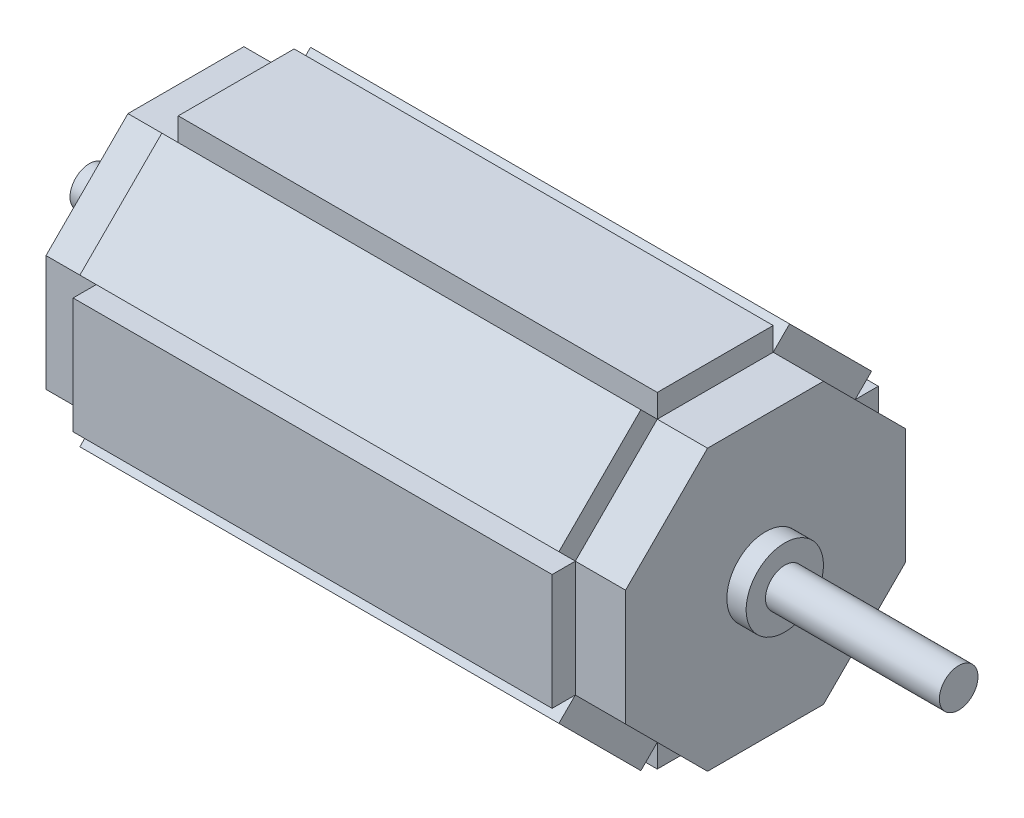
SolidWorks part; units mm, degrees
ref_plane "前视基准面" through (0, 0, 0) normal (0, 0, 1) x (1, 0, 0)
ref_plane "上视基准面" through (0, 0, 0) normal (0, 1, 0) x (1, 0, 0)
ref_plane "右视基准面" through (0, 0, 0) normal (1, 0, 0) x (0, 0, -1)
other "Configuration Table"
sketch "草图1" plane through (0, 0, 0) normal (1, 0, 0) x (0, 0, -1)
  line L1 (7.2426, -3) -> (7.2426, 3)
  line L2 (7.2426, 3) -> (3, 7.2426)
  line L3 (3, 7.2426) -> (-3, 7.2426)
  line L4 (-3, 7.2426) -> (-7.2426, 3)
  line L5 (-7.2426, 3) -> (-7.2426, -3)
  line L6 (-7.2426, -3) -> (-3, -7.2426)
  line L7 (-3, -7.2426) -> (3, -7.2426)
  line L8 (3, -7.2426) -> (7.2426, -3)
  circle A0 centre (0, 0) radius 7.2426 construction
  dimension "D1" = 6
extrude "凸台-拉伸1" add sketch "草图1" along normal blind 30
sketch "草图2" plane through (0, 7.2426, 0) normal (0, 1, 0) x (1, 0, 0)
  line L0 (9.4384, -2.3461) -> (9.352, -2.1662)
  line L1 (9.352, -2.1662) -> (9.8774, -1.7488)
  line L2 (9.8774, -1.7488) -> (9.9997, -1.8064)
  line L3 (11.1224, -1.9863) -> (11.4319, -2.0078)
  line L4 (11.4319, -2.0078) -> (11.6478, -2.0151)
  line L5 (11.6478, -2.0151) -> (11.655, -1.5833)
  line L6 (9.9134, -0.9068) -> (9.8702, -0.7341)
  line L7 (9.8702, -0.7341) -> (10.0933, -0.5901)
  line L8 (10.0933, -0.5901) -> (10.1005, -0.5829)
  line L9 (9.8126, 0.6981) -> (10.2732, 1.1299)
  line L10 (11.6406, 0.7557) -> (11.6765, 0.7629)
  line L11 (11.6765, 0.7629) -> (11.6622, 0.9284)
  line L12 (11.5902, 1.4249) -> (11.9284, 1.684)
  line L13 (11.9284, 1.684) -> (11.5686, 1.7272)
  line L14 (11.5686, 1.7272) -> (10.5467, 1.828)
  line L15 (9.6975, 1.828) -> (9.6399, 1.828)
  line L16 (9.6399, 1.828) -> (9.5247, 2.0151)
  line L17 (9.5247, 2.0151) -> (10.1365, 2.4037)
  line L18 (12.3746, 2.0367) -> (12.5186, 2.051)
  line L19 (12.5186, 2.051) -> (12.5617, 1.8711)
  line L20 (12.5617, 1.8711) -> (12.1515, 1.648)
  line L21 (12.0292, 1.1011) -> (11.9644, 0)
  line L22 (11.9788, -1.9647) -> (11.9788, -2.0294)
  line L23 (11.9788, -2.0294) -> (12.6265, -2.0294)
  line L24 (12.6265, -2.0294) -> (12.6625, -2.159)
  line L25 (12.6625, -2.159) -> (12.2451, -2.4541)
  line L26 (12.3386, -1.6264) -> (12.3962, -1.4897)
  line L27 (13.339, -1.7488) -> (13.3462, -1.3889)
  line L28 (13.3606, -0.6909) -> (12.5761, -0.5829)
  line L29 (12.5761, -0.5829) -> (12.5401, -0.4822)
  line L30 (12.5401, -0.4822) -> (12.8496, -0.2591)
  line L31 (13.2886, 0.3886) -> (13.5261, 0.6621)
  line L32 (12.792, 0.7197) -> (12.7489, 0.8564)
  line L33 (12.7489, 0.8564) -> (12.9216, 0.9715)
  line L34 (12.9216, 0.9715) -> (12.9288, 1.0579)
  line L35 (12.9288, 1.0579) -> (12.9, 1.4249)
  line L36 (12.7057, 2.0655) -> (13.0727, 2.4037)
  line L37 (13.0727, 2.4037) -> (13.1231, 2.3533)
  line L38 (13.4613, 2.1662) -> (13.6197, 2.1302)
  line L39 (14.0802, 2.0583) -> (14.4473, 2.3821)
  line L40 (14.4473, 2.3821) -> (14.548, 2.2741)
  line L41 (14.548, 2.2741) -> (14.5336, 2.2454)
  line L42 (14.3249, 0.5829) -> (14.109, 0.3742)
  line L43 (14.109, 0.3742) -> (14.0011, 0.403)
  line L44 (14.0011, 0.403) -> (14.0011, 0.5757)
  line L45 (14.0011, 0.5757) -> (13.7276, 0.6333)
  line L46 (13.7276, 0.6333) -> (13.6916, 0.5038)
  line L47 (13.6412, -1.7632) -> (13.6485, -1.8279)
  line L48 (13.6485, -1.8279) -> (14.145, -1.9215)
  line L49 (14.1306, -0.4174) -> (14.5984, -0.0648)
  line L50 (14.5984, -0.0648) -> (14.6632, -0.1799)
  line L51 (14.4473, -1.8208) -> (14.4688, -1.9791)
  line L52 (14.4688, -1.9791) -> (14.8935, -2.0223)
  line L53 (14.8935, -2.0223) -> (14.951, -2.1086)
  line L54 (14.951, -2.1086) -> (14.5336, -2.3605)
  line L55 (11.6765, -0.6837) -> (11.6765, 0.4534)
  line L56 (11.2303, 0.511) -> (10.777, 0.5613)
  line L57 (10.777, 0.5613) -> (10.3164, 0.5829)
  line L58 (11.3527, -0.6909) -> (11.6765, -0.6837)
  line L59 (8.6618, -2.4842) -> (8.6618, 2.5158) construction
  spline S0 degree 3 poles (12.2451, -2.4541) (11.9788, -2.3917) (11.4463, -2.2669) (10.5755, -2.2669) knots 0 0 0 0 1 1 1 1
  spline S1 degree 3 poles (10.5755, -2.2669) (10.3955, -2.2669) (10.0357, -2.2669) (9.4384, -2.3461) knots 1 1 1 1 2 2 2 2
  spline S2 degree 3 poles (9.9997, -1.8064) (10.0765, -1.8399) (10.23, -1.9071) (10.669, -1.9503) knots 5 5 5 5 6 6 6 6
  spline S3 degree 3 poles (10.669, -1.9503) (10.7698, -1.9599) (10.9713, -1.9791) (11.1224, -1.9863) knots 6 6 6 6 7 7 7 7
  spline S4 degree 3 poles (11.655, -1.5833) (11.6598, -1.4537) (11.6694, -1.1946) (11.6622, -1.0003) knots 10 10 10 10 11 11 11 11
  spline S5 degree 3 poles (11.6622, -1.0003) (11.4631, -0.962) (11.0648, -0.8852) (10.4315, -0.8852) knots 11 11 11 11 12 12 12 12
  spline S6 degree 3 poles (10.4315, -0.8852) (10.3452, -0.8852) (10.1725, -0.8852) (9.9134, -0.9068) knots 12 12 12 12 13 13 13 13
  spline S7 degree 3 poles (10.1005, -0.5829) (10.0981, -0.523) (10.0933, -0.403) (10.0789, -0.2123) knots 16 16 16 16 17 17 17 17
  spline S8 degree 3 poles (10.0789, -0.2123) (10.0741, -0.1487) (10.0645, -0.0216) (10.0285, 0.1295) knots 17 17 17 17 18 18 18 18
  spline S9 degree 3 poles (10.0285, 0.1295) (10.0165, 0.1967) (9.9925, 0.331) (9.9494, 0.4606) knots 18 18 18 18 19 19 19 19
  spline S10 degree 3 poles (9.9494, 0.4606) (9.9349, 0.5038) (9.9062, 0.5901) (9.8126, 0.6981) knots 19 19 19 19 20 20 20 20
  spline S11 degree 3 poles (10.2732, 1.1299) (10.3356, 1.0675) (10.4603, 0.9428) (10.7194, 0.878) knots 21 21 21 21 22 22 22 22
  spline S12 degree 3 poles (10.7194, 0.878) (10.8417, 0.8468) (11.0864, 0.7844) (11.6406, 0.7557) knots 22 22 22 22 23 23 23 23
  spline S13 degree 3 poles (11.6622, 0.9284) (11.6598, 0.9692) (11.655, 1.0507) (11.6406, 1.1839) knots 25 25 25 25 26 26 26 26
  spline S14 degree 3 poles (11.6406, 1.1839) (11.6358, 1.2283) (11.6262, 1.317) (11.5902, 1.4249) knots 26 26 26 26 27 27 27 27
  spline S15 degree 3 poles (10.5467, 1.828) (10.4747, 1.8351) (10.3308, 1.8495) (10.1221, 1.8495) knots 30 30 30 30 31 31 31 31
  spline S16 degree 3 poles (10.1221, 1.8495) (10.0477, 1.8495) (9.899, 1.8495) (9.6975, 1.828) knots 31 31 31 31 32 32 32 32
  spline S17 degree 3 poles (10.1365, 2.4037) (10.2036, 2.3365) (10.338, 2.2022) (10.6978, 2.1158) knots 35 35 35 35 36 36 36 36
  spline S18 degree 3 poles (10.6978, 2.1158) (10.7793, 2.0966) (10.9425, 2.0583) (11.2879, 2.0367) knots 36 36 36 36 37 37 37 37
  spline S19 degree 3 poles (11.2879, 2.0367) (11.3719, 2.0271) (11.5398, 2.0079) (11.8565, 2.0079) knots 37 37 37 37 38 38 38 38
  spline S20 degree 3 poles (11.8565, 2.0079) (11.9524, 2.0079) (12.1443, 2.0079) (12.3746, 2.0367) knots 38 38 38 38 39 39 39 39
  spline S21 degree 3 poles (12.1515, 1.648) (12.1179, 1.5641) (12.0508, 1.3962) (12.0292, 1.1011) knots 42 42 42 42 43 43 43 43
  spline S22 degree 3 poles (11.9644, 0) (11.962, -0.0911) (11.9572, -0.2735) (11.9572, -0.8132) knots 44 44 44 44 45 45 45 45
  spline S23 degree 3 poles (11.9572, -0.8132) (11.9572, -1.0051) (11.9572, -1.3889) (11.9788, -1.9647) knots 45 45 45 45 46 46 46 46
  spline S24 degree 3 poles (14.5336, -2.3605) (14.3705, -2.2981) (14.0442, -2.1734) (13.0511, -1.8567) knots 0 0 0 0 1 1 1 1
  spline S25 degree 3 poles (13.0511, -1.8567) (12.9719, -1.8327) (12.8136, -1.7848) (12.3386, -1.6264) knots 1 1 1 1 2 2 2 2
  spline S26 degree 3 poles (12.3962, -1.4897) (12.5665, -1.5401) (12.9072, -1.6409) (13.339, -1.7488) knots 3 3 3 3 4 4 4 4
  spline S27 degree 3 poles (13.3462, -1.3889) (13.3534, -1.257) (13.3678, -0.9931) (13.3606, -0.6909) knots 5 5 5 5 6 6 6 6
  spline S28 degree 3 poles (12.8496, -0.2591) (12.8832, -0.2927) (12.9504, -0.3598) (13.0727, -0.4066) knots 9 9 9 9 10 10 10 10
  spline S29 degree 3 poles (13.0727, -0.4066) (13.1135, -0.4222) (13.195, -0.4534) (13.3678, -0.475) knots 10 10 10 10 11 11 11 11
  spline S30 degree 3 poles (13.3678, -0.475) (13.3678, -0.3022) (13.3678, 0.0432) (13.2886, 0.3886) knots 11 11 11 11 12 12 12 12
  spline S31 degree 3 poles (13.5261, 0.6621) (13.3918, 0.6813) (13.1231, 0.7197) (12.792, 0.7197) knots 13 13 13 13 14 14 14 14
  spline S32 degree 3 poles (12.9, 1.4249) (12.8928, 1.4945) (12.8784, 1.6336) (12.8388, 1.7848) knots 18 18 18 18 19 19 19 19
  spline S33 degree 3 poles (12.8388, 1.7848) (12.8256, 1.8351) (12.7993, 1.9359) (12.7057, 2.0655) knots 19 19 19 19 20 20 20 20
  spline S34 degree 3 poles (13.1231, 2.3533) (13.1711, 2.3101) (13.267, 2.2238) (13.4613, 2.1662) knots 22 22 22 22 23 23 23 23
  spline S35 degree 3 poles (13.6197, 2.1302) (13.6916, 2.1134) (13.8355, 2.0798) (14.0802, 2.0583) knots 24 24 24 24 25 25 25 25
  spline S36 degree 3 poles (14.5336, 2.2454) (14.5049, 2.1926) (14.4473, 2.087) (14.4113, 1.9143) knots 28 28 28 28 29 29 29 29
  spline S37 degree 3 poles (14.4113, 1.9143) (14.3969, 1.8472) (14.3681, 1.7128) (14.3465, 1.4897) knots 29 29 29 29 30 30 30 30
  spline S38 degree 3 poles (14.3465, 1.4897) (14.3321, 1.3602) (14.3033, 1.1011) (14.3033, 0.9068) knots 30 30 30 30 31 31 31 31
  spline S39 degree 3 poles (14.3033, 0.9068) (14.3033, 0.854) (14.3033, 0.7484) (14.3249, 0.5829) knots 31 31 31 31 32 32 32 32
  spline S40 degree 3 poles (13.6916, 0.5038) (13.6652, 0.4126) (13.6125, 0.2303) (13.6125, -0.1727) knots 37 37 37 37 38 38 38 38
  spline S41 degree 3 poles (13.6125, -0.1727) (13.6101, -0.2207) (13.6053, -0.3167) (13.6053, -0.5973) knots 38 38 38 38 39 39 39 39
  spline S42 degree 3 poles (13.6053, -0.5973) (13.6053, -0.77) (13.6053, -1.1155) (13.6412, -1.7632) knots 39 39 39 39 40 40 40 40
  spline S43 degree 3 poles (14.145, -1.9215) (14.1546, -1.8663) (14.1738, -1.756) (14.1882, -1.4321) knots 42 42 42 42 43 43 43 43
  spline S44 degree 3 poles (14.1882, -1.4321) (14.193, -1.3458) (14.2026, -1.1731) (14.2026, -1.0507) knots 43 43 43 43 44 44 44 44
  spline S45 degree 3 poles (14.2026, -1.0507) (14.2026, -0.938) (14.2026, -0.7125) (14.1306, -0.4174) knots 44 44 44 44 45 45 45 45
  spline S46 degree 3 poles (14.6632, -0.1799) (14.6296, -0.2303) (14.5624, -0.331) (14.5192, -0.439) knots 47 47 47 47 48 48 48 48
  spline S47 degree 3 poles (14.5192, -0.439) (14.5049, -0.475) (14.4761, -0.5469) (14.4617, -0.7125) knots 48 48 48 48 49 49 49 49
  spline S48 degree 3 poles (14.4617, -0.7125) (14.4521, -0.8084) (14.4329, -1.0003) (14.4329, -1.353) knots 49 49 49 49 50 50 50 50
  spline S49 degree 3 poles (14.4329, -1.353) (14.4329, -1.4561) (14.4329, -1.6624) (14.4473, -1.8208) knots 50 50 50 50 51 51 51 51
  spline S50 degree 3 poles (14.0227, 0.8132) (14.0467, 1.0051) (14.0946, 1.3889) (14.0874, 1.8136) knots 4 4 4 4 5 5 5 5
  spline S51 degree 3 poles (13.2382, 0.9715) (13.3414, 0.9404) (13.5477, 0.878) (14.0227, 0.8132) knots 3 3 3 3 4 4 4 4
  spline S52 degree 3 poles (13.1591, 1.9503) (13.1663, 1.7608) (13.1807, 1.3818) (13.2382, 0.9715) knots 2 2 2 2 3 3 3 3
  spline S53 degree 3 poles (13.6448, 1.8999) (13.5141, 1.9191) (13.2526, 1.9575) (13.1591, 1.9503) knots 1 1 1 1 2 2 2 2
  spline S54 degree 3 poles (14.0874, 1.8136) (14.0706, 1.8231) (14.0371, 1.8424) (13.6448, 1.8999) knots 0 0 0 0 1 1 1 1
  spline S55 degree 3 poles (11.6765, 0.4534) (11.6286, 0.463) (11.5326, 0.4822) (11.2303, 0.511) knots 1 1 1 1 2 2 2 2
  spline S56 degree 3 poles (10.3164, 0.5829) (10.3164, 0.355) (10.3164, -0.1007) (10.4171, -0.5326) knots 4 4 4 4 5 5 5 5
  spline S57 degree 3 poles (10.4171, -0.5326) (10.4555, -0.5494) (10.5323, -0.5829) (10.669, -0.6189) knots 5 5 5 5 6 6 6 6
  spline S58 degree 3 poles (10.669, -0.6189) (10.7194, -0.6309) (10.8201, -0.6549) (11.0001, -0.6693) knots 6 6 6 6 7 7 7 7
  spline S59 degree 3 poles (11.0001, -0.6693) (11.06, -0.6741) (11.18, -0.6837) (11.3527, -0.6909) knots 7 7 7 7 8 8 8 8
  dimension "D1" = 5
sketch "草图3" plane through (0, 7.2426, 0) normal (0, 1, 0) x (1, 0, 0)
  line L0 (16.0742, -2.3589) -> (15.9878, -2.179)
  line L1 (15.9878, -2.179) -> (16.5131, -1.7616)
  line L2 (16.5131, -1.7616) -> (16.6355, -1.8191)
  line L3 (17.7582, -1.999) -> (18.0677, -2.0206)
  line L4 (18.0677, -2.0206) -> (18.2836, -2.0278)
  line L5 (18.2836, -2.0278) -> (18.2908, -1.596)
  line L6 (16.5492, -0.9195) -> (16.506, -0.7468)
  line L7 (16.506, -0.7468) -> (16.7291, -0.6029)
  line L8 (16.7291, -0.6029) -> (16.7363, -0.5957)
  line L9 (16.4484, 0.6853) -> (16.909, 1.1171)
  line L10 (18.2763, 0.7429) -> (18.3123, 0.7501)
  line L11 (18.3123, 0.7501) -> (18.2979, 0.9156)
  line L12 (18.226, 1.4122) -> (18.5642, 1.6713)
  line L13 (18.5642, 1.6713) -> (18.2044, 1.7144)
  line L14 (18.2044, 1.7144) -> (17.1825, 1.8152)
  line L15 (16.3332, 1.8152) -> (16.2757, 1.8152)
  line L16 (16.2757, 1.8152) -> (16.1605, 2.0023)
  line L17 (16.1605, 2.0023) -> (16.7723, 2.3909)
  line L18 (19.0104, 2.0239) -> (19.1544, 2.0383)
  line L19 (19.1544, 2.0383) -> (19.1975, 1.8584)
  line L20 (19.1975, 1.8584) -> (18.7873, 1.6353)
  line L21 (18.665, 1.0883) -> (18.6002, -0.0128)
  line L22 (18.6146, -1.9774) -> (18.6146, -2.0422)
  line L23 (18.6146, -2.0422) -> (19.2623, -2.0422)
  line L24 (19.2623, -2.0422) -> (19.2983, -2.1717)
  line L25 (19.2983, -2.1717) -> (18.8809, -2.4668)
  line L26 (18.9744, -1.6392) -> (19.032, -1.5025)
  line L27 (19.9748, -1.7616) -> (19.9819, -1.4017)
  line L28 (19.9964, -0.7036) -> (19.2119, -0.5957)
  line L29 (19.2119, -0.5957) -> (19.1759, -0.4949)
  line L30 (19.1759, -0.4949) -> (19.4854, -0.2718)
  line L31 (19.9244, 0.3759) -> (20.1619, 0.6493)
  line L32 (19.4278, 0.7069) -> (19.3847, 0.8436)
  line L33 (19.3847, 0.8436) -> (19.5574, 0.9588)
  line L34 (19.5574, 0.9588) -> (19.5646, 1.0451)
  line L35 (19.5646, 1.0451) -> (19.5358, 1.4122)
  line L36 (19.3415, 2.0527) -> (19.7085, 2.3909)
  line L37 (19.7085, 2.3909) -> (19.7589, 2.3406)
  line L38 (20.0971, 2.1534) -> (20.2554, 2.1175)
  line L39 (20.716, 2.0455) -> (21.0831, 2.3693)
  line L40 (21.0831, 2.3693) -> (21.1838, 2.2614)
  line L41 (21.1838, 2.2614) -> (21.1694, 2.2326)
  line L42 (20.9607, 0.5702) -> (20.7448, 0.3615)
  line L43 (20.7448, 0.3615) -> (20.6369, 0.3903)
  line L44 (20.6369, 0.3903) -> (20.6369, 0.563)
  line L45 (20.6369, 0.563) -> (20.3634, 0.6206)
  line L46 (20.3634, 0.6206) -> (20.3274, 0.491)
  line L47 (20.277, -1.7759) -> (20.2842, -1.8407)
  line L48 (20.2842, -1.8407) -> (20.7808, -1.9343)
  line L49 (20.7664, -0.4302) -> (21.2342, -0.0775)
  line L50 (21.2342, -0.0775) -> (21.299, -0.1927)
  line L51 (21.0831, -1.8335) -> (21.1046, -1.9918)
  line L52 (21.1046, -1.9918) -> (21.5292, -2.035)
  line L53 (21.5292, -2.035) -> (21.5868, -2.1214)
  line L54 (21.5868, -2.1214) -> (21.1694, -2.3732)
  line L55 (18.3123, -0.6964) -> (18.3123, 0.4406)
  line L56 (17.8661, 0.4982) -> (17.4127, 0.5486)
  line L57 (17.4127, 0.5486) -> (16.9522, 0.5702)
  line L58 (17.9885, -0.7036) -> (18.3123, -0.6964)
  spline S0 degree 3 poles (18.8809, -2.4668) (18.6146, -2.4044) (18.082, -2.2797) (17.2112, -2.2797) knots 0 0 0 0 1 1 1 1
  spline S1 degree 3 poles (17.2112, -2.2797) (17.0313, -2.2797) (16.6715, -2.2797) (16.0742, -2.3589) knots 1 1 1 1 2 2 2 2
  spline S2 degree 3 poles (16.6355, -1.8191) (16.7123, -1.8527) (16.8658, -1.9199) (17.3048, -1.9631) knots 5 5 5 5 6 6 6 6
  spline S3 degree 3 poles (17.3048, -1.9631) (17.4056, -1.9726) (17.6071, -1.9918) (17.7582, -1.999) knots 6 6 6 6 7 7 7 7
  spline S4 degree 3 poles (18.2908, -1.596) (18.2955, -1.4665) (18.3051, -1.2074) (18.2979, -1.0131) knots 10 10 10 10 11 11 11 11
  spline S5 degree 3 poles (18.2979, -1.0131) (18.0988, -0.9747) (17.7006, -0.898) (17.0673, -0.898) knots 11 11 11 11 12 12 12 12
  spline S6 degree 3 poles (17.0673, -0.898) (16.9809, -0.898) (16.8082, -0.898) (16.5492, -0.9195) knots 12 12 12 12 13 13 13 13
  spline S7 degree 3 poles (16.7363, -0.5957) (16.7339, -0.5357) (16.7291, -0.4158) (16.7147, -0.2251) knots 16 16 16 16 17 17 17 17
  spline S8 degree 3 poles (16.7147, -0.2251) (16.7099, -0.1615) (16.7003, -0.0344) (16.6643, 0.1168) knots 17 17 17 17 18 18 18 18
  spline S9 degree 3 poles (16.6643, 0.1168) (16.6523, 0.184) (16.6283, 0.3183) (16.5851, 0.4478) knots 18 18 18 18 19 19 19 19
  spline S10 degree 3 poles (16.5851, 0.4478) (16.5707, 0.491) (16.542, 0.5774) (16.4484, 0.6853) knots 19 19 19 19 20 20 20 20
  spline S11 degree 3 poles (16.909, 1.1171) (16.9713, 1.0548) (17.0961, 0.93) (17.3552, 0.8652) knots 21 21 21 21 22 22 22 22
  spline S12 degree 3 poles (17.3552, 0.8652) (17.4775, 0.834) (17.7222, 0.7717) (18.2763, 0.7429) knots 22 22 22 22 23 23 23 23
  spline S13 degree 3 poles (18.2979, 0.9156) (18.2955, 0.9564) (18.2908, 1.038) (18.2763, 1.1711) knots 25 25 25 25 26 26 26 26
  spline S14 degree 3 poles (18.2763, 1.1711) (18.2716, 1.2155) (18.2619, 1.3042) (18.226, 1.4122) knots 26 26 26 26 27 27 27 27
  spline S15 degree 3 poles (17.1825, 1.8152) (17.1105, 1.8224) (16.9665, 1.8368) (16.7578, 1.8368) knots 30 30 30 30 31 31 31 31
  spline S16 degree 3 poles (16.7578, 1.8368) (16.6835, 1.8368) (16.5348, 1.8368) (16.3332, 1.8152) knots 31 31 31 31 32 32 32 32
  spline S17 degree 3 poles (16.7723, 2.3909) (16.8394, 2.3238) (16.9737, 2.1894) (17.3336, 2.1031) knots 35 35 35 35 36 36 36 36
  spline S18 degree 3 poles (17.3336, 2.1031) (17.4151, 2.0839) (17.5783, 2.0455) (17.9237, 2.0239) knots 36 36 36 36 37 37 37 37
  spline S19 degree 3 poles (17.9237, 2.0239) (18.0077, 2.0143) (18.1756, 1.9951) (18.4923, 1.9951) knots 37 37 37 37 38 38 38 38
  spline S20 degree 3 poles (18.4923, 1.9951) (18.5882, 1.9951) (18.7801, 1.9951) (19.0104, 2.0239) knots 38 38 38 38 39 39 39 39
  spline S21 degree 3 poles (18.7873, 1.6353) (18.7537, 1.5513) (18.6866, 1.3834) (18.665, 1.0883) knots 42 42 42 42 43 43 43 43
  spline S22 degree 3 poles (18.6002, -0.0128) (18.5978, -0.1039) (18.593, -0.2862) (18.593, -0.826) knots 44 44 44 44 45 45 45 45
  spline S23 degree 3 poles (18.593, -0.826) (18.593, -1.0179) (18.593, -1.4017) (18.6146, -1.9774) knots 45 45 45 45 46 46 46 46
  spline S24 degree 3 poles (21.1694, -2.3732) (21.0063, -2.3109) (20.68, -2.1862) (19.6869, -1.8695) knots 0 0 0 0 1 1 1 1
  spline S25 degree 3 poles (19.6869, -1.8695) (19.6077, -1.8455) (19.4494, -1.7975) (18.9744, -1.6392) knots 1 1 1 1 2 2 2 2
  spline S26 degree 3 poles (19.032, -1.5025) (19.2023, -1.5528) (19.543, -1.6536) (19.9748, -1.7616) knots 3 3 3 3 4 4 4 4
  spline S27 degree 3 poles (19.9819, -1.4017) (19.9892, -1.2698) (20.0036, -1.0059) (19.9964, -0.7036) knots 5 5 5 5 6 6 6 6
  spline S28 degree 3 poles (19.4854, -0.2718) (19.519, -0.3054) (19.5861, -0.3726) (19.7085, -0.4194) knots 9 9 9 9 10 10 10 10
  spline S29 degree 3 poles (19.7085, -0.4194) (19.7492, -0.4349) (19.8308, -0.4661) (20.0036, -0.4877) knots 10 10 10 10 11 11 11 11
  spline S30 degree 3 poles (20.0036, -0.4877) (20.0036, -0.315) (20.0036, 0.0304) (19.9244, 0.3759) knots 11 11 11 11 12 12 12 12
  spline S31 degree 3 poles (20.1619, 0.6493) (20.0275, 0.6685) (19.7589, 0.7069) (19.4278, 0.7069) knots 13 13 13 13 14 14 14 14
  spline S32 degree 3 poles (19.5358, 1.4122) (19.5286, 1.4818) (19.5142, 1.6209) (19.4746, 1.772) knots 18 18 18 18 19 19 19 19
  spline S33 degree 3 poles (19.4746, 1.772) (19.4614, 1.8224) (19.435, 1.9232) (19.3415, 2.0527) knots 19 19 19 19 20 20 20 20
  spline S34 degree 3 poles (19.7589, 2.3406) (19.8068, 2.2974) (19.9028, 2.211) (20.0971, 2.1534) knots 22 22 22 22 23 23 23 23
  spline S35 degree 3 poles (20.2554, 2.1175) (20.3274, 2.1007) (20.4713, 2.0671) (20.716, 2.0455) knots 24 24 24 24 25 25 25 25
  spline S36 degree 3 poles (21.1694, 2.2326) (21.1406, 2.1798) (21.0831, 2.0743) (21.0471, 1.9016) knots 28 28 28 28 29 29 29 29
  spline S37 degree 3 poles (21.0471, 1.9016) (21.0327, 1.8344) (21.0039, 1.7001) (20.9823, 1.477) knots 29 29 29 29 30 30 30 30
  spline S38 degree 3 poles (20.9823, 1.477) (20.9679, 1.3474) (20.9391, 1.0883) (20.9391, 0.894) knots 30 30 30 30 31 31 31 31
  spline S39 degree 3 poles (20.9391, 0.894) (20.9391, 0.8413) (20.9391, 0.7357) (20.9607, 0.5702) knots 31 31 31 31 32 32 32 32
  spline S40 degree 3 poles (20.3274, 0.491) (20.301, 0.3998) (20.2482, 0.2176) (20.2482, -0.1855) knots 37 37 37 37 38 38 38 38
  spline S41 degree 3 poles (20.2482, -0.1855) (20.2458, -0.2334) (20.2411, -0.3294) (20.2411, -0.6101) knots 38 38 38 38 39 39 39 39
  spline S42 degree 3 poles (20.2411, -0.6101) (20.2411, -0.7828) (20.2411, -1.1282) (20.277, -1.7759) knots 39 39 39 39 40 40 40 40
  spline S43 degree 3 poles (20.7808, -1.9343) (20.7904, -1.8791) (20.8096, -1.7687) (20.8239, -1.4449) knots 42 42 42 42 43 43 43 43
  spline S44 degree 3 poles (20.8239, -1.4449) (20.8288, -1.3585) (20.8384, -1.1858) (20.8384, -1.0635) knots 43 43 43 43 44 44 44 44
  spline S45 degree 3 poles (20.8384, -1.0635) (20.8384, -0.9507) (20.8384, -0.7252) (20.7664, -0.4302) knots 44 44 44 44 45 45 45 45
  spline S46 degree 3 poles (21.299, -0.1927) (21.2654, -0.243) (21.1982, -0.3438) (21.155, -0.4517) knots 47 47 47 47 48 48 48 48
  spline S47 degree 3 poles (21.155, -0.4517) (21.1406, -0.4877) (21.1118, -0.5597) (21.0975, -0.7252) knots 48 48 48 48 49 49 49 49
  spline S48 degree 3 poles (21.0975, -0.7252) (21.0878, -0.8212) (21.0686, -1.0131) (21.0686, -1.3657) knots 49 49 49 49 50 50 50 50
  spline S49 degree 3 poles (21.0686, -1.3657) (21.0686, -1.4689) (21.0686, -1.6752) (21.0831, -1.8335) knots 50 50 50 50 51 51 51 51
  spline S50 degree 3 poles (20.6584, 0.8005) (20.6825, 0.9924) (20.7304, 1.3762) (20.7232, 1.8008) knots 4 4 4 4 5 5 5 5
  spline S51 degree 3 poles (19.874, 0.9588) (19.9772, 0.9276) (20.1835, 0.8652) (20.6584, 0.8005) knots 3 3 3 3 4 4 4 4
  spline S52 degree 3 poles (19.7948, 1.9376) (19.802, 1.748) (19.8164, 1.369) (19.874, 0.9588) knots 2 2 2 2 3 3 3 3
  spline S53 degree 3 poles (20.2806, 1.8872) (20.1499, 1.9064) (19.8884, 1.9447) (19.7948, 1.9376) knots 1 1 1 1 2 2 2 2
  spline S54 degree 3 poles (20.7232, 1.8008) (20.7064, 1.8104) (20.6728, 1.8296) (20.2806, 1.8872) knots 0 0 0 0 1 1 1 1
  spline S55 degree 3 poles (18.3123, 0.4406) (18.2643, 0.4503) (18.1684, 0.4694) (17.8661, 0.4982) knots 1 1 1 1 2 2 2 2
  spline S56 degree 3 poles (16.9522, 0.5702) (16.9522, 0.3423) (16.9522, -0.1135) (17.0529, -0.5453) knots 4 4 4 4 5 5 5 5
  spline S57 degree 3 poles (17.0529, -0.5453) (17.0913, -0.5621) (17.1681, -0.5957) (17.3048, -0.6317) knots 5 5 5 5 6 6 6 6
  spline S58 degree 3 poles (17.3048, -0.6317) (17.3552, -0.6437) (17.4559, -0.6676) (17.6359, -0.682) knots 6 6 6 6 7 7 7 7
  spline S59 degree 3 poles (17.6359, -0.682) (17.6958, -0.6868) (17.8158, -0.6964) (17.9885, -0.7036) knots 7 7 7 7 8 8 8 8
sketch "草图4" plane through (30, 0, 0) normal (1, 0, 0) x (0, 0, -1)
  circle A0 centre (0, 0) radius 1
  dimension "D1" = 2
extrude "凸台-拉伸2" add sketch "草图4" along normal blind 10
sketch "草图5" plane through (30, 0, 0) normal (1, 0, 0) x (0, 0, -1)
  circle A0 centre (0, 0) radius 2
  dimension "D1" = 4
extrude "凸台-拉伸3" add sketch "草图5" along normal blind 1 contours A0
sketch "草图6" plane through (0, 0, 0) normal (-1, 0, 0) x (0, 0, 1)
  circle A0 centre (0, 0) radius 1 construction
  circle A1 centre (0, 0) radius 1
extrude "凸台-拉伸4" add sketch "草图6" along normal blind 5
sketch "草图7" plane through (0, 0, 0) normal (-1, 0, 0) x (0, 0, 1)
  circle A0 centre (0, 0) radius 2 construction
  circle A1 centre (0, 0) radius 2
extrude "凸台-拉伸5" add sketch "草图7" along normal blind 1
sketch "草图8" plane through (0, 7.2426, 0) normal (0, 1, 0) x (1, 0, 0)
  line L0 (2.6018, 0) -> (27.3982, 0) construction
  line L1 (2.6018, 3) -> (27.3982, 3)
  line L2 (2.6018, 3) -> (2.6018, -3)
  line L3 (2.6018, -3) -> (27.3982, -3)
  line L4 (27.3982, 3) -> (27.3982, -3)
  line L5 (2.6018, 3) -> (27.3982, -3) construction
  line L6 (2.6018, -3) -> (27.3982, 3) construction
  line L7 (15, 0) -> (15, -3) construction
  line L9 (30, 3) -> (0, 3) construction
  point P0 (15, 0)
  point P9 (15, 3)
  dimension "D1" = 6
extrude "凸台-拉伸6" add sketch "草图8" along normal blind 1.2
pattern_circular "阵列(圆周)1" count 8 over 360 about axis through (0, 0, 0) along (1, 0, 0) of "凸台-拉伸6"
